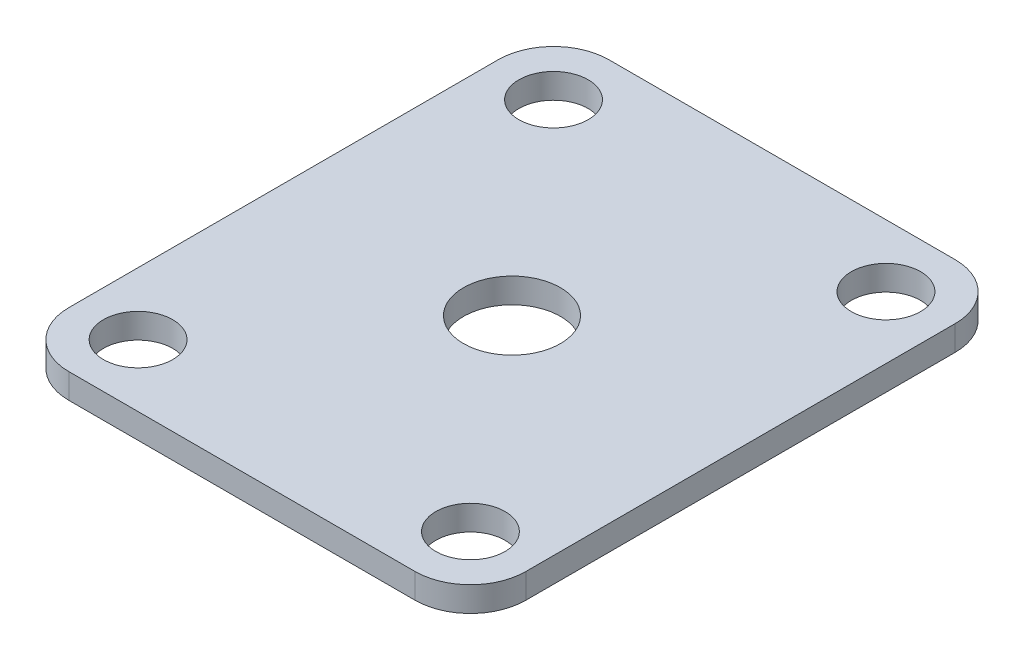
SolidWorks part; units mm, degrees
ref_plane "Front Plane" through (0, 0, 0) normal (0, 0, 1) x (1, 0, 0)
ref_plane "Top Plane" through (0, 0, 0) normal (0, 1, 0) x (1, 0, 0)
ref_plane "Right Plane" through (0, 0, 0) normal (1, 0, 0) x (0, 0, -1)
sketch "Sketch1" plane through (0, 0, 0) normal (0, 1, 0) x (1, 0, 0)
  line L0 (0, -19.5) -> (0, -15) construction
  line L1 (16.5, -19.5) -> (-16.5, -19.5)
  line L2 (16.5, -19.5) -> (16.5, 19.5)
  line L3 (16.5, 19.5) -> (-16.5, 19.5)
  line L4 (-16.5, -19.5) -> (-16.5, 19.5)
  line L5 (16.5, -19.5) -> (-16.5, 19.5) construction
  line L6 (16.5, 19.5) -> (-16.5, -19.5) construction
  line L7 (16.5, 0) -> (10.6097, 0) construction
  circle A1 centre (12, -15) radius 2.5
  circle A2 centre (12, 15) radius 2.5
  circle A3 centre (-12, -15) radius 2.5
  circle A4 centre (-12, 15) radius 2.5
  circle A5 centre (0, 0) radius 3.5
  point P0 (0, 0)
  dimension "D3" = 4.5
  dimension "D1" = 33
  dimension "D2" = 39
  dimension "D4" = 4.5
extrude "Boss-Extrude1" add sketch "Sketch1" along normal blind 1.8
fillet "Fillet1" radius 4 1 edges at (-16.5, 0.9, -19.5)
fillet "Fillet2" radius 4 1 edges at (16.5, 0.9, -19.5)
fillet "Fillet3" radius 4 1 edges at (16.5, 0.9, 19.5)
fillet "Fillet4" radius 4 1 edges at (-16.5, 0.9, 19.5)
